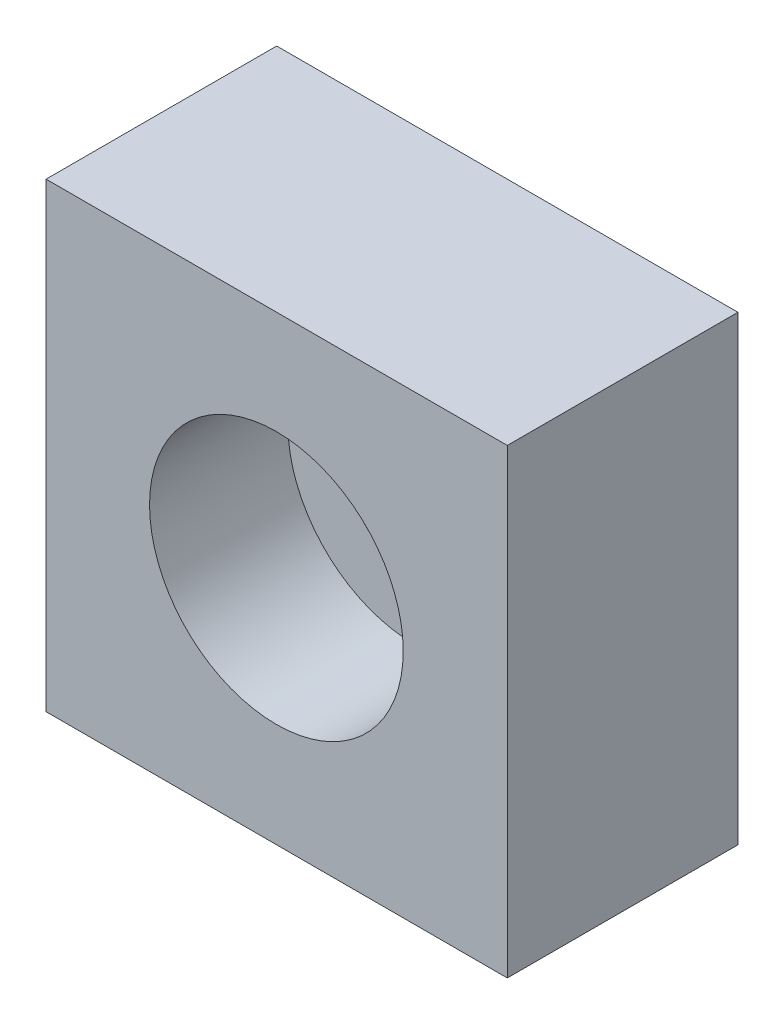
SolidWorks part; units mm, degrees
ref_plane "前视基准面" through (0, 0, 0) normal (0, 0, 1) x (1, 0, 0)
ref_plane "上视基准面" through (0, 0, 0) normal (0, 1, 0) x (1, 0, 0)
ref_plane "右视基准面" through (0, 0, 0) normal (1, 0, 0) x (0, 0, -1)
other "Configuration Table"
sketch "草图1" plane through (0, 0, 0) normal (0, 0, 1) x (1, 0, 0)
  line L1 (0, 0) -> (20, 0)
  line L2 (0, 0) -> (0, 20)
  line L3 (0, 20) -> (20, 20)
  line L4 (20, 0) -> (20, 20)
extrude "BaseBox" add sketch "草图1" along normal blind 10
hole_wizard "Hole_BlindCbore_thru_depth" positions "草图3" profile "草图2" counterbore size "M6" standard "ISO"
sketch "草图3" plane through (0, 0, 10) normal (0, 0, 1) x (1, 0, 0)
  point P0 (9.9865, 10.0143)
sketch "草图2" plane through (9.9865, 10.0143, 10) normal (1, 0, 0) x (0, -1, 0)
  line L0 (0, 0) -> (0, 10)
  line L1 (0, 10) -> (3, 10)
  line L3 (3, 10) -> (3, 6)
  line L4 (3, 6) -> (5.5, 6)
  line L5 (5.5, 6) -> (5.5, 0)
  line L7 (5.5, 0) -> (0, 0)
  line L11 (0, -6.35) -> (0, 107.95) construction
  dimension "通孔孔直径" = 6
  dimension "通孔孔深度" = 10
  dimension "柱形沉头孔直径" = 11
  dimension "柱形沉头孔深度" = 6
